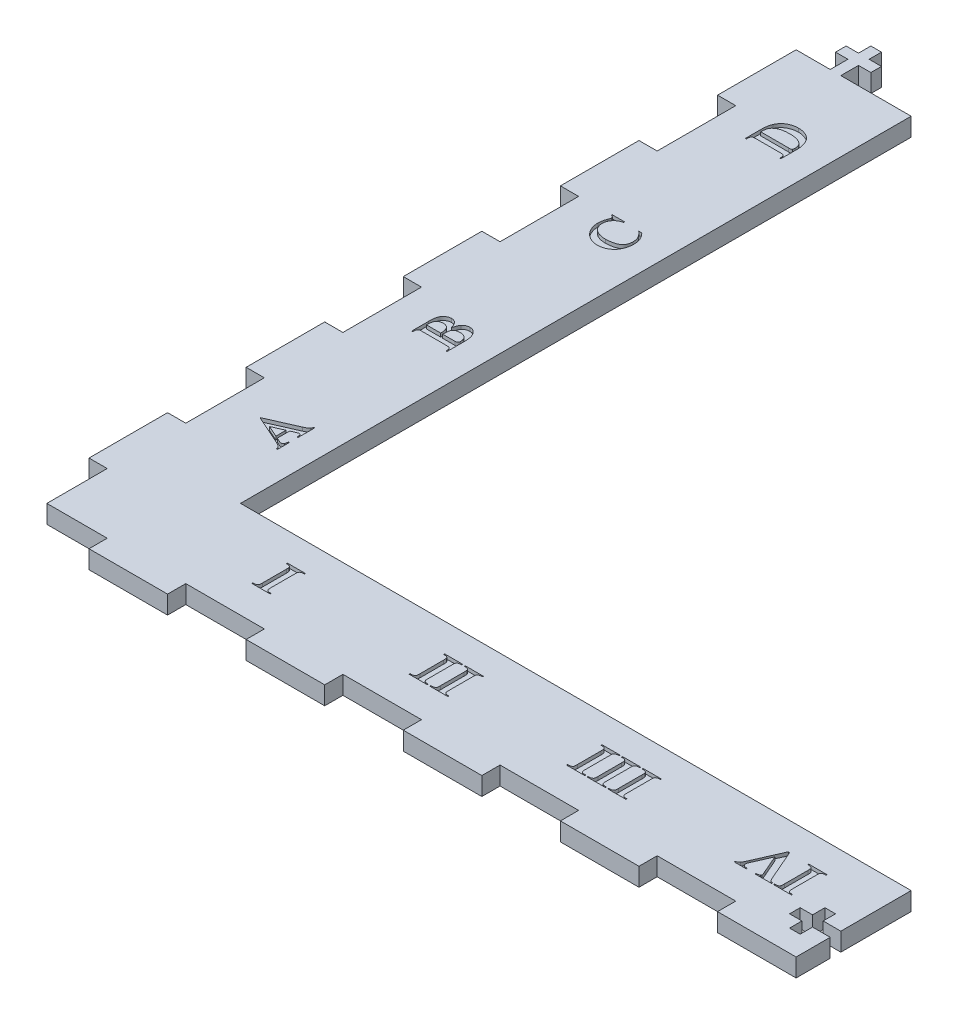
SolidWorks part; units mm, degrees
ref_plane "Front Plane" through (0, 0, 0) normal (0, 0, 1) x (1, 0, 0)
ref_plane "Top Plane" through (0, 0, 0) normal (0, 1, 0) x (1, 0, 0)
ref_plane "Right Plane" through (0, 0, 0) normal (1, 0, 0) x (0, 0, -1)
sketch "Sketch1" plane through (0, 0, 0) normal (0, 1, 0) x (1, 0, 0)
  line L1 (0, 0) -> (222.25, 0)
  line L2 (0, 0) -> (0, 222.25)
  line L3 (0, 222.25) -> (222.25, 222.25)
  line L4 (222.25, 0) -> (222.25, 222.25)
  dimension "D1" = 222.25
extrude "Boss-Extrude1" add sketch "Sketch1" along normal blind 5.15
sketch "Sketch2" plane through (0, 5.15, 0) normal (0, 1, 0) x (1, 0, 0)
  line L0 (5.15, 22.225) -> (5.15, 44.45) construction
  line L1 (0, 0) -> (5.15, 0)
  line L2 (0, 0) -> (0, 22.225)
  line L3 (0, 22.225) -> (5.15, 22.225)
  line L4 (5.15, 0) -> (5.15, 22.225)
  line L5 (0, 44.45) -> (5.15, 44.45)
  line L6 (0, 44.45) -> (0, 66.675)
  line L7 (0, 66.675) -> (5.15, 66.675)
  line L8 (5.15, 44.45) -> (5.15, 66.675)
  line L9 (5.15, 66.675) -> (5.15, 88.9) construction
  line L10 (0, 88.9) -> (5.15, 88.9)
  line L11 (0, 88.9) -> (0, 111.125)
  line L12 (0, 111.125) -> (5.15, 111.125)
  line L13 (5.15, 88.9) -> (5.15, 111.125)
  line L14 (5.15, 111.125) -> (5.15, 133.35) construction
  line L15 (0, 133.35) -> (5.15, 133.35)
  line L16 (0, 133.35) -> (0, 155.575)
  line L17 (0, 155.575) -> (5.15, 155.575)
  line L18 (5.15, 133.35) -> (5.15, 155.575)
  line L19 (5.15, 155.575) -> (5.15, 177.8) construction
  line L20 (0, 177.8) -> (5.15, 177.8)
  line L21 (0, 177.8) -> (0, 200.025)
  line L22 (0, 200.025) -> (5.15, 200.025)
  line L23 (5.15, 177.8) -> (5.15, 200.025)
  line L24 (5.15, 200.025) -> (5.15, 222.25) construction
  line L25 (222.25, 222.25) -> (0, 222.25) construction
  line L27 (0, 0) -> (222.25, 0) construction
  line L28 (5.15, 5.15) -> (22.225, 5.15)
  line L29 (5.15, 5.15) -> (5.15, 0)
  line L30 (5.15, 0) -> (22.225, 0)
  line L31 (22.225, 5.15) -> (22.225, 0)
  line L32 (22.225, 5.15) -> (0, 5.15) construction
  line L33 (44.45, 0) -> (66.675, 0)
  line L34 (44.45, 0) -> (44.45, 5.15)
  line L35 (44.45, 5.15) -> (66.675, 5.15)
  line L36 (66.675, 0) -> (66.675, 5.15)
  line L37 (44.45, 5.15) -> (22.225, 5.15) construction
  line L38 (88.9, 0) -> (111.125, 0)
  line L39 (88.9, 0) -> (88.9, 5.15)
  line L40 (88.9, 5.15) -> (111.125, 5.15)
  line L41 (111.125, 0) -> (111.125, 5.15)
  line L42 (88.9, 5.15) -> (66.675, 5.15) construction
  line L43 (133.35, 0) -> (155.575, 0)
  line L44 (133.35, 0) -> (133.35, 5.15)
  line L45 (133.35, 5.15) -> (155.575, 5.15)
  line L46 (155.575, 0) -> (155.575, 5.15)
  line L47 (133.35, 5.15) -> (111.125, 5.15) construction
  line L48 (177.8, 0) -> (200.025, 0)
  line L49 (177.8, 0) -> (177.8, 5.15)
  line L50 (177.8, 5.15) -> (200.025, 5.15)
  line L51 (200.025, 0) -> (200.025, 5.15)
  line L52 (177.8, 5.15) -> (155.575, 5.15) construction
  line L53 (200.025, 5.15) -> (222.25, 5.15) construction
  line L54 (222.25, 0) -> (222.25, 222.25) construction
  line M34 (0, 222.25) -> (0, 0)
  line M35 (0, 0) -> (222.25, 0)
  dimension "D2" = 5.15
  dimension "D1" = 5
  dimension "D3" = 4
extrude "Cut-Extrude1" cut sketch "Sketch2" against normal through all contours L31 L28 L4 M35 | L4 L3 M35 M34 | L36 L35 L34 M35 | L41 L40 L39 M35 | L46 L45 L44 M35 | L51 L50 L49 M35 | L5 L8 L7 M34 | L15 L18 L17 M34 | L10 L13 L12 M34 | L21 L22 L23 L20
sketch "Sketch3" plane through (0, 5.15, 0) normal (0, 1, 0) x (1, 0, 0)
  line L1 (222.25, 222.25) -> (32.5438, 222.25)
  line L2 (222.25, 222.25) -> (222.25, 32.5437)
  line L3 (222.25, 32.5437) -> (32.5438, 32.5437)
  line L4 (32.5438, 222.25) -> (32.5438, 32.5437)
  dimension "D1" = 189.7062
extrude "Cut-Extrude2" cut sketch "Sketch3" against normal through all
sketch "Sketch4" plane through (0, 5.15, 0) normal (0, 1, 0) x (1, 0, 0)
  line L0 (5.15, 200.025) -> (5.15, 222.25) construction
  line L1 (32.5438, 222.25) -> (0, 222.25) construction
  line L2 (5.15, 211.1375) -> (32.5438, 211.1375) construction
  line L3 (32.5438, 222.25) -> (32.5438, 32.5437) construction
  line L4 (9.65, 222.25) -> (9.65, 227.25)
  line L5 (9.65, 227.25) -> (6.15, 227.25)
  line L6 (6.15, 227.25) -> (6.15, 230.25)
  line L7 (6.15, 230.25) -> (9.65, 230.25)
  line L8 (9.65, 230.25) -> (9.65, 233.75)
  line L9 (9.65, 233.75) -> (12.65, 233.75)
  line L10 (12.65, 233.75) -> (12.65, 230.25)
  line L11 (12.65, 230.25) -> (16.15, 230.25)
  line L12 (16.15, 230.25) -> (16.15, 227.25)
  line L13 (16.15, 227.25) -> (12.65, 227.25)
  line L14 (12.65, 227.25) -> (12.65, 222.25)
  line L15 (12.65, 222.25) -> (9.65, 222.25)
  line L16 (11.15, 233.75) -> (11.15, 211.1375) construction
  dimension "D1" = 3
  dimension "D2" = 1
  dimension "D3" = 5
  dimension "D4" = 3.5
extrude "Boss-Extrude2" add sketch "Sketch4" against normal up to surface (5.15 mm away) up to face at (60.9842, 0, -60.9842)
sketch "Sketch5" plane through (0, 5.15, 0) normal (0, 1, 0) x (1, 0, 0)
  line L0 (222.25, 9.65) -> (217.25, 9.65)
  line L1 (222.25, 0) -> (222.25, 32.5437) construction
  line L2 (217.25, 9.65) -> (217.25, 6.15)
  line L3 (217.25, 6.15) -> (214.25, 6.15)
  line L4 (214.25, 6.15) -> (214.25, 9.65)
  line L5 (214.25, 9.65) -> (210.75, 9.65)
  line L6 (210.75, 9.65) -> (210.75, 12.65)
  line L7 (210.75, 12.65) -> (214.25, 12.65)
  line L8 (214.25, 12.65) -> (214.25, 16.15)
  line L9 (214.25, 16.15) -> (217.25, 16.15)
  line L10 (217.25, 16.15) -> (217.25, 12.65)
  line L11 (217.25, 12.65) -> (222.25, 12.65)
  line L12 (222.25, 12.65) -> (222.25, 9.65)
  line L13 (12.65, 230.25) -> (12.65, 233.75) construction
  line L15 (217.25, 6.15) -> (217.25, 5.15) construction
  line L16 (177.8, 5.15) -> (200.025, 5.15) construction
  line L17 (6.15, 230.25) -> (5.15, 230.25) construction
  line L18 (5.15, 177.8) -> (5.15, 200.025) construction
  line L19 (9.65, 227.25) -> (9.65, 222.25) construction
  line L20 (12.65, 233.75) -> (9.65, 233.75) construction
extrude "Cut-Extrude3" cut sketch "Sketch5" against normal through all
sketch "Sketch6" plane through (0, 5.15, 0) normal (0, 1, 0) x (1, 0, 0)
  line L0 (32.5438, 32.5437) -> (0, 32.5437) construction
  line L1 (0, 44.45) -> (0, 22.225) construction
  line L2 (24.5438, 32.5437) -> (24.5438, 79.9703) construction
  line L3 (24.5438, 79.9703) -> (24.5438, 127.3969) construction
  line L4 (24.5438, 127.3969) -> (24.5438, 174.8234) construction
  line L5 (24.5438, 174.8234) -> (24.5438, 222.25) construction
  line L6 (32.5438, 222.25) -> (12.65, 222.25) construction
  line L7 (32.5438, 32.5437) -> (32.5438, 0) construction
  line L8 (22.225, 0) -> (44.45, 0) construction
  line L9 (32.5438, 24.5437) -> (79.9703, 24.5437) construction
  line L10 (79.9703, 24.5437) -> (127.3969, 24.5437) construction
  line L11 (127.3969, 24.5437) -> (174.8234, 24.5437) construction
  line L12 (174.8234, 24.5437) -> (222.25, 24.5437) construction
  line L13 (222.25, 12.65) -> (222.25, 32.5437) construction
  line L14 (24.5438, 32.5437) -> (24.5438, 24.5437) construction
  line L15 (24.5438, 24.5437) -> (32.5438, 24.5437) construction
  line L16 (32.5438, 222.25) -> (32.5438, 32.5437) construction
  text T0 "A" font "Times New Roman" height 10
  text T1 "B" font "Times New Roman" height 10
  text T2 "C" font "Times New Roman" height 10
  text T3 "D" font "Times New Roman" height 10
  text T4 "I" font "Times New Roman" height 10
  text T5 "II" font "Times New Roman" height 10
  text T6 "III" font "Times New Roman" height 10
  text T7 "IV" font "Times New Roman" height 10
  dimension "D1" = 8
extrude "Cut-Extrude4" cut sketch "Sketch6" against normal blind 1
equation "\"standard_thickness\"= 5.15mm"
equation "\"D1@Boss-Extrude1\"=\"standard_thickness\""
equation "\"D2@Sketch2\"=\"standard_thickness\""
